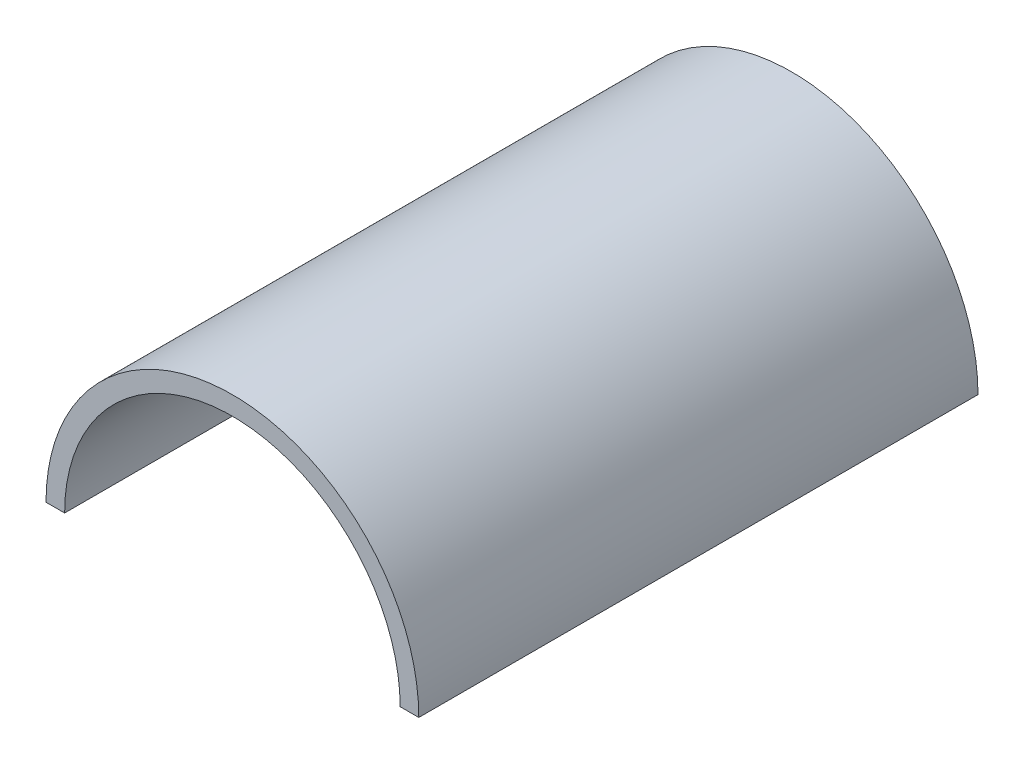
SolidWorks part; units mm, degrees
ref_plane "Plano frontal" through (0, 0, 0) normal (0, 0, 1) x (1, 0, 0)
ref_plane "Plano superior" through (0, 0, 0) normal (0, 1, 0) x (1, 0, 0)
ref_plane "Plano direito" through (0, 0, 0) normal (1, 0, 0) x (0, 0, -1)
sketch "Esboço1" plane through (0, 0, 0) normal (0, 0, 1) x (1, 0, 0)
  circle A0 centre (0, 0) radius 18
  circle A1 centre (0, 0) radius 20
  dimension "D1" = 36
  dimension "D2" = 2
extrude "Ressalto-extrusão1" add sketch "Esboço1" along normal blind 60
sketch "Esboço2" plane through (0, 0, 0) normal (0, 1, 0) x (1, 0, 0)
  line L1 (-20, 0) -> (20, 0)
  line L2 (-20, 0) -> (-20, -60)
  line L3 (-20, -60) -> (20, -60)
  line L4 (20, 0) -> (20, -60)
extrude "Corte-extrusão1" cut sketch "Esboço2" against normal blind 60
